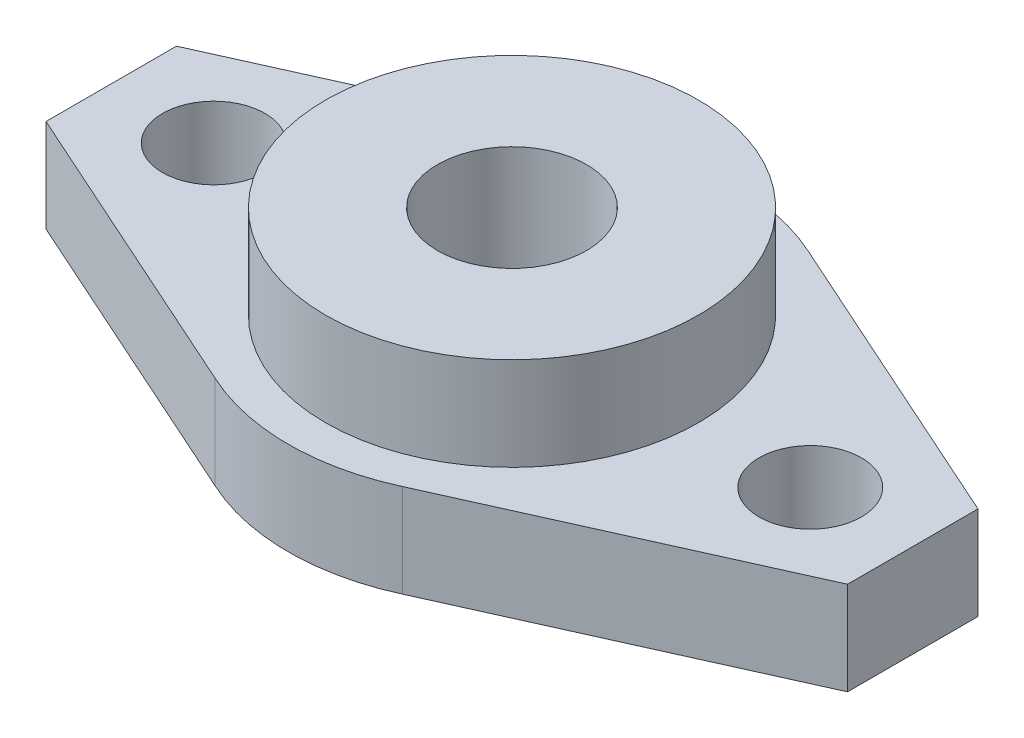
SolidWorks part; units mm, degrees
ref_plane "Front Plane" through (0, 0, 0) normal (0, 0, 1) x (1, 0, 0)
ref_plane "Top Plane" through (0, 0, 0) normal (0, 1, 0) x (1, 0, 0)
ref_plane "Right Plane" through (0, 0, 0) normal (1, 0, 0) x (0, 0, -1)
sketch "Sketch1" plane through (0, 0, 0) normal (0, 1, 0) x (1, 0, 0)
  line L0 (-21.5, 3.5) -> (-21.5, -3.5)
  line L1 (-21.5, 3.5) -> (-5.0254, 10.897)
  line L2 (-21.5, -3.5) -> (-5.0254, -10.897)
  line L3 (21.5, -3.5) -> (21.5, 3.5)
  line L4 (21.5, 3.5) -> (5.0254, 10.897)
  line L5 (21.5, -3.5) -> (5.0254, -10.897)
  circle A0 centre (16, 0) radius 2.75
  circle A1 centre (-16, 0) radius 2.75
  circle A2 centre (0, 0) radius 12
  dimension "D1" = 5.5
  dimension "D2" = 5.5
  dimension "D5" = 24
  dimension "D3" = 32
  dimension "D4" = 16
  dimension "D6" = 43
  dimension "D7" = 7
  dimension "D8" = 3.5
  dimension "D9" = 7
extrude "Boss-Extrude1" add sketch "Sketch1" along normal blind 5 contours A2 L5 L3 L4 A0 | A2 | A2 L1 L0 L2 A1
sketch "Sketch2" plane through (0, 5, 0) normal (0, 1, 0) x (1, 0, 0)
  circle A0 centre (0, 0) radius 10
  dimension "D1" = 20
extrude "Boss-Extrude2" add sketch "Sketch2" along normal blind 5
sketch "Sketch3" plane through (0, 10, 0) normal (0, 1, 0) x (1, 0, 0)
  circle A0 centre (0, 0) radius 4
  dimension "D1" = 8
extrude "Cut-Extrude1" cut sketch "Sketch3" against normal up to next
